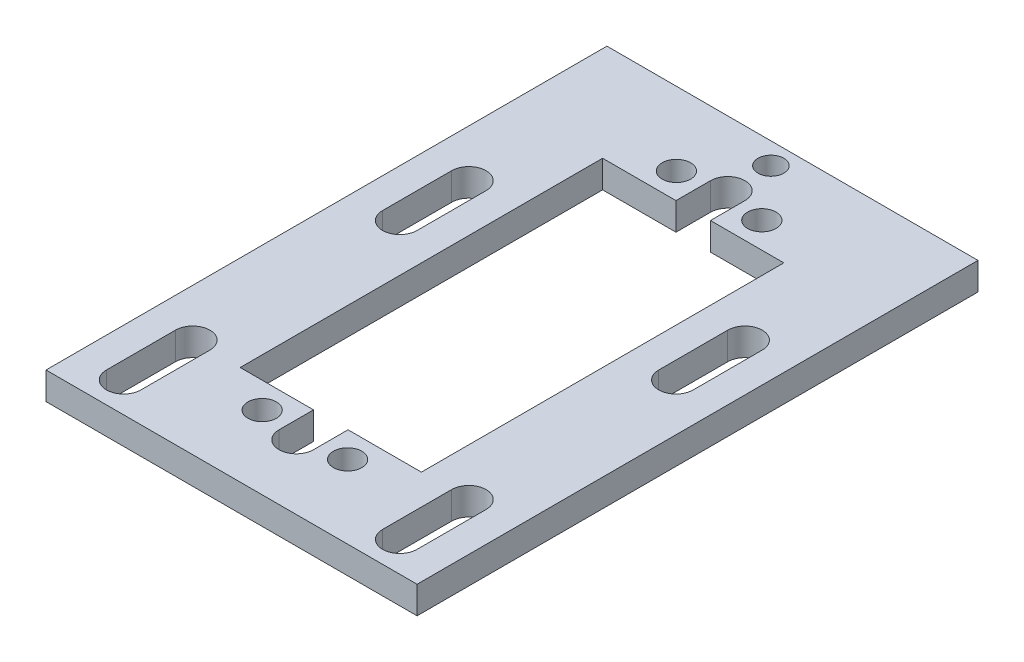
SolidWorks part; units mm, degrees
ref_plane "Front" through (0, 0, 0) normal (0, 0, 1) x (1, 0, 0)
ref_plane "Top" through (0, 0, 0) normal (0, 1, 0) x (1, 0, 0)
ref_plane "Right" through (0, 0, 0) normal (1, 0, 0) x (0, 0, -1)
sketch "Sketch1" plane through (0, 0, 0) normal (0, 1, 0) x (1, 0, 0)
  line L0 (0, 21) -> (0, 25)
  line L1 (-10.5, -21) -> (10.5, -21)
  line L2 (-10.5, -21) -> (-10.5, 21)
  line L3 (-10.5, 21) -> (10.5, 21)
  line L4 (10.5, -21) -> (10.5, 21)
  line L5 (-10.5, -21) -> (10.5, 21) construction
  line L6 (-10.5, 21) -> (10.5, -21) construction
  line L7 (-21.5, 32.5) -> (21.5, 32.5)
  line L8 (-21.5, 32.5) -> (-21.5, -32.5)
  line L9 (-21.5, -32.5) -> (21.5, -32.5)
  line L10 (21.5, 32.5) -> (21.5, -32.5)
  line L11 (-21.5, 32.5) -> (21.5, -32.5) construction
  line L12 (-21.5, -32.5) -> (21.5, 32.5) construction
  line L13 (-2, 25) -> (-2, 21)
  line L14 (2, 25) -> (2, 21)
  line L15 (0, 24) -> (0, -24)
  line L16 (-4.95, -24) -> (4.95, -24)
  line L17 (-4.95, 24) -> (4.95, 24)
  line L18 (-10.5, 0) -> (10.5, 0)
  line L19 (2, -25) -> (2, -21)
  line L20 (-2, -25) -> (-2, -21)
  arc A0 (-2, 25) -> (2, 25) centre (0, 25) cw
  circle A1 centre (4.95, 24) radius 1.65
  circle A2 centre (-4.95, 24) radius 1.65
  circle A3 centre (-4.95, -24) radius 1.65
  circle A4 centre (4.95, -24) radius 1.65
  arc A5 (-2, -25) -> (2, -25) centre (0, -25) ccw
  point P0 (0, 0)
  point P6 (0, 0)
  point P20 (0, 0)
  point P23 (0, -24)
  point P26 (0, 24)
  dimension "D5" = 2
  dimension "D4" = 4
  dimension "D9" = 43
  dimension "D1" = 21
  dimension "D2" = 42
  dimension "D3" = 65
  dimension "D6" = 9.9
  dimension "D7" = 9.9
  dimension "D8" = 48
extrude "Boss-Extrude1" add sketch "Sketch1" along normal blind 3.175
sketch "Sketch3" plane through (0, 3.175, 0) normal (0, 1, 0) x (1, 0, 0)
  line L0 (-16, -25) -> (16, -25)
  line L1 (-16, -21) -> (-16, -29) construction
  line L2 (-14, -21) -> (-14, -29)
  line L3 (-18, -21) -> (-18, -29)
  line L4 (0, 0) -> (0, -25)
  line L5 (16, -21) -> (16, -29) construction
  line L6 (14, -21) -> (14, -29)
  line L7 (18, -21) -> (18, -29)
  line L8 (-16, 11) -> (-16, 3) construction
  line L9 (-14, 11) -> (-14, 3)
  line L10 (-18, 11) -> (-18, 3)
  line L11 (16, 11) -> (16, 3) construction
  line L12 (14, 11) -> (14, 3)
  line L13 (18, 11) -> (18, 3)
  arc A0 (-14, -21) -> (-18, -21) centre (-16, -21) ccw
  arc A1 (-18, -29) -> (-14, -29) centre (-16, -29) ccw
  arc A2 (14, -21) -> (18, -21) centre (16, -21) cw
  arc A3 (18, -29) -> (14, -29) centre (16, -29) cw
  arc A4 (-14, 11) -> (-18, 11) centre (-16, 11) ccw
  arc A5 (-18, 3) -> (-14, 3) centre (-16, 3) ccw
  arc A6 (14, 11) -> (18, 11) centre (16, 11) cw
  arc A7 (18, 3) -> (14, 3) centre (16, 3) cw
  point P3 (0, -25)
  point P6 (-16, -25)
  point P15 (16, -25)
  point P24 (-16, 7)
  point P31 (16, 7)
  dimension "D3" = 2
  dimension "D1" = 32
  dimension "D2" = 0
  dimension "D4" = 25
  dimension "D5" = 8
  dimension "D6" = 2
extrude "Cut-Extrude1" cut sketch "Sketch3" against normal blind 3.175
sketch "Sketch4" plane through (0, 3.175, 0) normal (0, 1, 0) x (1, 0, 0)
  line L0 (-21.5, 32.5) -> (-21.5, -32.5) construction
  line L1 (-21.5, 32.5) -> (21.5, 32.5) construction
  circle A0 centre (0, 30) radius 1.5
  dimension "D1" = 21.5
  dimension "D2" = 2.5
extrude "Cut-Extrude2" cut sketch "Sketch4" against normal blind 10
